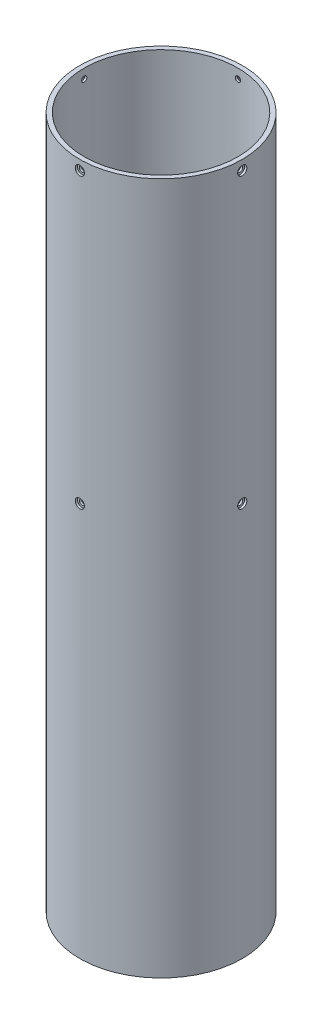
SolidWorks part; units mm, degrees
material "Hexcel AS4C (3000 Filaments)"
ref_plane "Front Plane" through (0, 0, 0) normal (0, 0, 1) x (1, 0, 0)
ref_plane "Top Plane" through (0, 0, 0) normal (0, 1, 0) x (1, 0, 0)
ref_plane "Right Plane" through (0, 0, 0) normal (1, 0, 0) x (0, 0, -1)
sketch "Sketch1" plane through (0, 0, 0) normal (0, 1, 0) x (1, 0, 0)
  circle A0 centre (0, 0) radius 50.8
  dimension "D1" = 101.6
extrude "Body Extrusion" add sketch "Sketch1" along normal blind 457.2 thin
ref_plane "Plane1" through (0, 0, 53.721) normal (0, 0, 1) x (1, 0, 0)
sketch "Sketch2" plane through (0, 0, 53.721) normal (0, 0, 1) x (1, 0, 0)
  line L0 (0, 457.2) -> (0, 0) construction
  line L1 (53.721, 457.2) -> (-53.721, 457.2) construction
  line L3 (50.8, 457.2) -> (-50.8, 457.2) construction
  circle A0 centre (0, 450.85) radius 1.7526
  dimension "D1" = 3.5052
  dimension "D2" = 6.35
extrude "Upper Bulkhead Holes" cut sketch "Sketch2" against normal up to next
pattern_circular "Upper Bulkhead Hole Pattern" count 4 over 360 about axis through (0, 457.2, 0) along (0, -1, 0) of "Upper Bulkhead Holes"
sketch "Sketch3" plane through (0, 0, 53.721) normal (0, 0, 1) x (1, 0, 0)
  line L0 (0, 457.2) -> (0, 0) construction
  line L1 (53.721, 457.2) -> (-53.721, 457.2) construction
  line L2 (50.8, 457.2) -> (-50.8, 457.2) construction
  circle A0 centre (0, 260.35) radius 1.7526
  dimension "D1" = 3.5052
  dimension "D2" = 260.35
  dimension "D3" = 196.85
extrude "Lower Bulkhead Holes" cut sketch "Sketch3" against normal up to next
pattern_circular "Lower Bulkhead Hole Pattern" count 4 over 360 about axis through (0, 457.2, 0) along (0, -1, 0) of "Lower Bulkhead Holes"
sketch "Sketch4" plane through (0, 0, 53.721) normal (0, 0, 1) x (1, 0, 0)
  line L0 (0, 457.2) -> (0, 0) construction
  line L1 (50.8, 457.2) -> (-50.8, 457.2) construction
  line L2 (-50.8, 0) -> (50.8, 0) construction
  circle A0 centre (0, 450.85) radius 3.0226
  circle A1 centre (0, 260.35) radius 3.0226
  circle A2 centre (0, 260.35) radius 1.7526 construction
  circle A3 centre (0, 450.85) radius 1.7526 construction
  dimension "D1" = 1.27
  dimension "D2" = 1.27
extrude "Countersink" cut sketch "Sketch4" against normal blind 1.524
pattern_circular "Countersink Pattern" count 4 over 360 about axis through (0, 0, 0) along (0, 1, 0) of "Countersink"
equation "\"D2@Sketch4\"=\"D1@Sketch4\""
